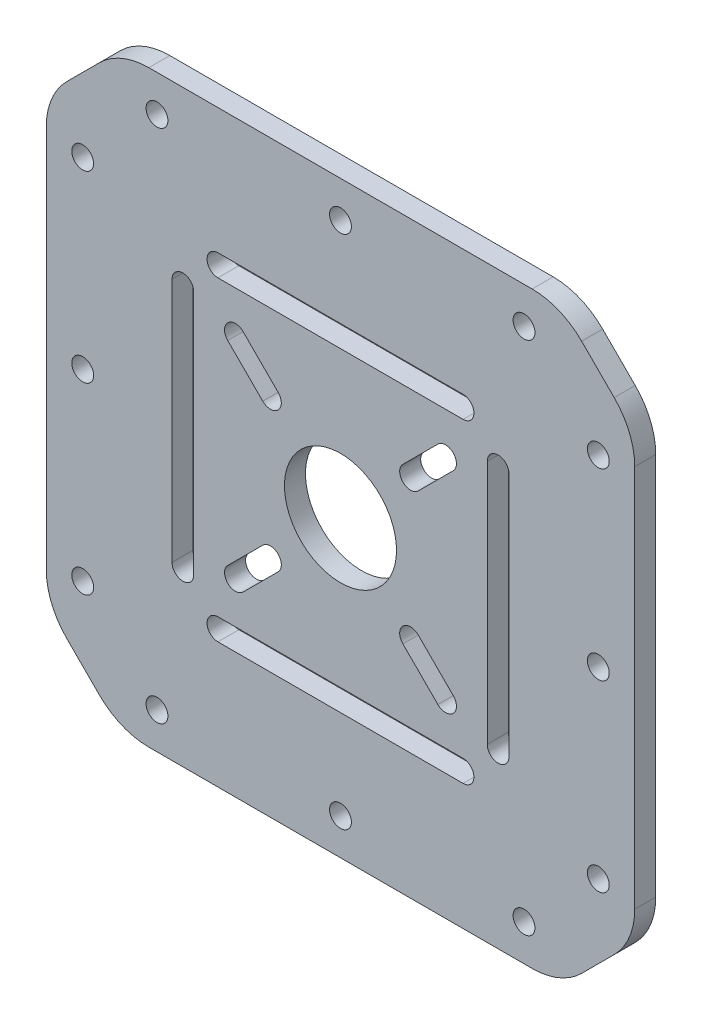
SolidWorks part; units mm, degrees
ref_plane "前视基准面" through (0, 0, 0) normal (0, 0, 1) x (1, 0, 0)
ref_plane "上视基准面" through (0, 0, 0) normal (0, 1, 0) x (1, 0, 0)
ref_plane "右视基准面" through (0, 0, 0) normal (1, 0, 0) x (0, 0, -1)
other "Configuration Table"
sketch "草图1" plane through (0, 0, 0) normal (0, 0, 1) x (1, 0, 0)
  line L0 (-36.8033, 26.1967) -> (-26.1967, 36.8033) construction
  line L7 (0, -42.1996) -> (0, 42.1996) construction
  line L8 (-31.5, 31.5) -> (31.5, 31.5) construction
  line L9 (42.1996, 0) -> (-42.1996, 0) construction
  line L10 (-31.5, 31.5) -> (-31.5, -31.5) construction
  line L11 (-31.5, -31.5) -> (31.5, -31.5) construction
  line L21 (31.5, 31.5) -> (31.5, -31.5) construction
  line L22 (-31.5, 31.5) -> (31.5, -31.5) construction
  line L23 (-31.5, -31.5) -> (31.5, 31.5) construction
  line L24 (-26.1967, 36.8033) -> (26.1967, 36.8033) construction
  line L25 (-17.5, 22.5) -> (17.5, 22.5) construction
  line L26 (-17.5, 22.5) -> (17.5, 22.5) construction
  line L31 (-17.5, -22.5) -> (17.5, -22.5) construction
  line L32 (-17.5, 24.05) -> (17.5, 24.05)
  line L33 (-17.5, 20.95) -> (17.5, 20.95)
  line L34 (-17.5, -24.05) -> (17.5, -24.05)
  line L35 (-17.5, -20.95) -> (17.5, -20.95)
  line L36 (-15, 15) -> (15, 15) construction
  line L37 (22.5, -17.5) -> (22.5, 17.5) construction
  line L38 (24.05, -17.5) -> (24.05, 17.5)
  line L39 (20.95, -17.5) -> (20.95, 17.5)
  line L40 (-22.5, -17.5) -> (-22.5, 17.5) construction
  line L41 (-24.05, -17.5) -> (-24.05, 17.5)
  line L42 (-20.95, -17.5) -> (-20.95, 17.5)
  line L43 (-10, 10) -> (10, 10) construction
  line L44 (-10, 10) -> (-10, -10) construction
  line L45 (-10, -10) -> (10, -10) construction
  line L46 (10, 10) -> (10, -10) construction
  line L47 (-10, 10) -> (10, -10) construction
  line L48 (-10, -10) -> (10, 10) construction
  line L49 (-15, 15) -> (-15, -15) construction
  line L50 (-15, -15) -> (15, -15) construction
  line L51 (15, 15) -> (15, -15) construction
  line L52 (10, 10) -> (15, 15) construction
  line L53 (8.904, 11.096) -> (13.904, 16.096)
  line L54 (11.096, 8.904) -> (16.096, 13.904)
  line L55 (-10, 10) -> (-15, 15) construction
  line L56 (-8.904, 11.096) -> (-13.904, 16.096)
  line L57 (-11.096, 8.904) -> (-16.096, 13.904)
  line L58 (-10, -10) -> (-15, -15) construction
  line L59 (-8.904, -11.096) -> (-13.904, -16.096)
  line L60 (-11.096, -8.904) -> (-16.096, -13.904)
  line L61 (10, -10) -> (15, -15) construction
  line L62 (8.904, -11.096) -> (13.904, -16.096)
  line L63 (11.096, -8.904) -> (16.096, -13.904)
  line L64 (-27.3579, 42) -> (27.3579, 42)
  line L65 (42, -27.3579) -> (42, 27.3579)
  line L66 (-42, -27.3579) -> (-42, 27.3579)
  line L67 (-27.3579, -42) -> (27.3579, -42)
  line L68 (-39.0711, 34.4289) -> (-34.4289, 39.0711)
  line L69 (34.4289, 39.0711) -> (39.0711, 34.4289)
  line L70 (39.0711, -34.4289) -> (34.4289, -39.0711)
  line L71 (-34.4289, -39.0711) -> (-39.0711, -34.4289)
  circle A20 centre (0, 0) radius 8
  arc A21 (-17.5, 24.05) -> (-17.5, 20.95) centre (-17.5, 22.5) ccw
  arc A22 (17.5, 20.95) -> (17.5, 24.05) centre (17.5, 22.5) ccw
  arc A23 (-17.5, -24.05) -> (-17.5, -20.95) centre (-17.5, -22.5) cw
  arc A24 (17.5, -20.95) -> (17.5, -24.05) centre (17.5, -22.5) cw
  arc A25 (24.05, -17.5) -> (20.95, -17.5) centre (22.5, -17.5) cw
  arc A26 (20.95, 17.5) -> (24.05, 17.5) centre (22.5, 17.5) cw
  arc A27 (-24.05, -17.5) -> (-20.95, -17.5) centre (-22.5, -17.5) ccw
  arc A28 (-20.95, 17.5) -> (-24.05, 17.5) centre (-22.5, 17.5) ccw
  arc A29 (8.904, 11.096) -> (11.096, 8.904) centre (10, 10) ccw
  arc A30 (16.096, 13.904) -> (13.904, 16.096) centre (15, 15) ccw
  arc A31 (-8.904, 11.096) -> (-11.096, 8.904) centre (-10, 10) cw
  arc A32 (-16.096, 13.904) -> (-13.904, 16.096) centre (-15, 15) cw
  arc A33 (-8.904, -11.096) -> (-11.096, -8.904) centre (-10, -10) ccw
  arc A34 (-16.096, -13.904) -> (-13.904, -16.096) centre (-15, -15) ccw
  arc A35 (8.904, -11.096) -> (11.096, -8.904) centre (10, -10) cw
  arc A36 (16.096, -13.904) -> (13.904, -16.096) centre (15, -15) cw
  circle A37 centre (-26.1967, 36.8033) radius 1.56
  circle A38 centre (-36.8033, 26.1967) radius 1.56
  circle A39 centre (26.1967, 36.8033) radius 1.56
  circle A40 centre (36.8033, 26.1967) radius 1.56
  circle A41 centre (36.8033, -26.1967) radius 1.56
  circle A42 centre (26.1967, -36.8033) radius 1.56
  circle A43 centre (-26.1967, -36.8033) radius 1.56
  circle A44 centre (-36.8033, -26.1967) radius 1.56
  circle A45 centre (0, 36.8033) radius 1.56
  circle A46 centre (36.8033, 0) radius 1.56
  circle A47 centre (0, -36.8033) radius 1.56
  circle A48 centre (-36.8033, 0) radius 1.56
  arc A49 (-27.3579, 42) -> (-34.4289, 39.0711) centre (-27.3579, 32) ccw
  arc A50 (-42, 27.3579) -> (-39.0711, 34.4289) centre (-32, 27.3579) cw
  arc A51 (-42, -27.3579) -> (-39.0711, -34.4289) centre (-32, -27.3579) ccw
  arc A52 (-27.3579, -42) -> (-34.4289, -39.0711) centre (-27.3579, -32) cw
  arc A53 (27.3579, -42) -> (34.4289, -39.0711) centre (27.3579, -32) ccw
  arc A54 (42, -27.3579) -> (39.0711, -34.4289) centre (32, -27.3579) cw
  arc A55 (42, 27.3579) -> (39.0711, 34.4289) centre (32, 27.3579) ccw
  arc A56 (27.3579, 42) -> (34.4289, 39.0711) centre (27.3579, 32) cw
  point P0 (0, 0)
  point P11 (-31.5, 31.5)
  point P46 (-31.5, 42)
  point P49 (-42, 31.5)
  point P52 (-42, -31.5)
  point P55 (-31.5, -42)
  point P58 (31.5, -42)
  point P61 (42, -31.5)
  point P64 (42, 31.5)
  point P73 (0, 22.5)
  point P78 (0, -22.5)
  point P86 (22.5, 0)
  point P93 (-22.5, 0)
  point P105 (12.5, 12.5)
  point P110 (-12.5, 12.5)
  point P115 (-12.5, -12.5)
  point P120 (12.5, -12.5)
  point P125 (31.5, 42)
  dimension "D2" = 3.12
  dimension "D3" = 52.3934
  dimension "D4" = 10
  dimension "D1" = 15
  dimension "D5" = 35
extrude "凸台-拉伸1" add sketch "草图1" along normal blind 3
